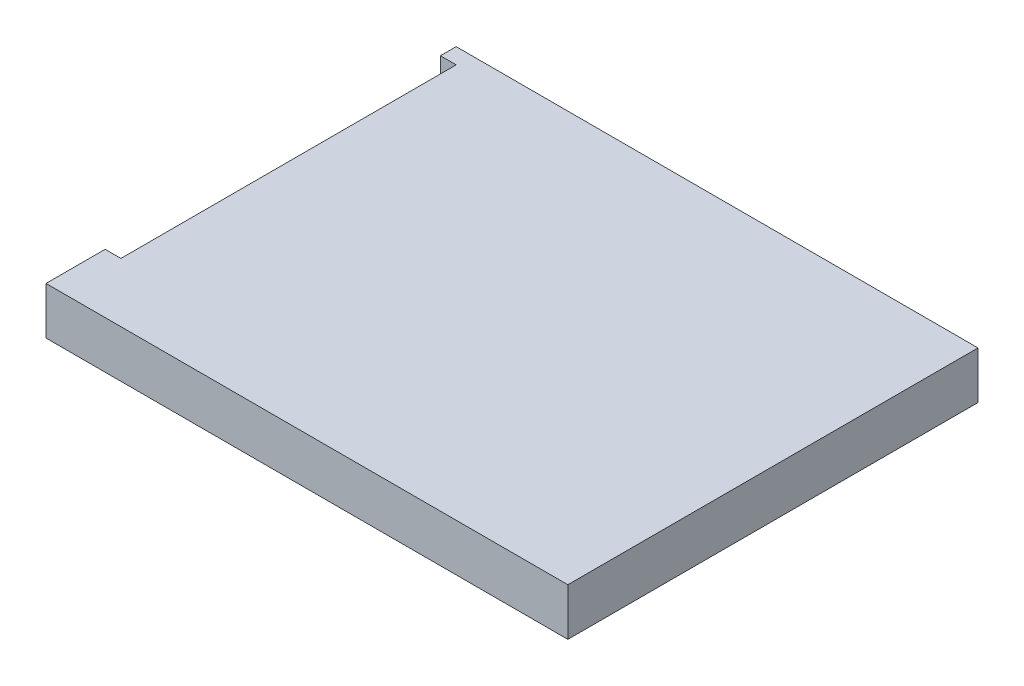
SolidWorks part; units mm, degrees
ref_plane "Front Plane" through (0, 0, 0) normal (0, 0, 1) x (1, 0, 0)
ref_plane "Top Plane" through (0, 0, 0) normal (0, 1, 0) x (1, 0, 0)
ref_plane "Right Plane" through (0, 0, 0) normal (1, 0, 0) x (0, 0, -1)
sketch "Sketch1" plane through (0, 0, 0) normal (0, 1, 0) x (1, 0, 0)
  line L1 (-108.0657, 72.5277) -> (101.9923, 72.5277)
  line L2 (-108.0657, 72.5277) -> (-108.0657, -92.5723)
  line L3 (-108.0657, -92.5723) -> (101.9923, -92.5723)
  line L4 (101.9923, 72.5277) -> (101.9923, -92.5723)
  dimension "D1" = 165.1
  dimension "D2" = 210.058
extrude "Boss-Extrude1" add sketch "Sketch1" along normal blind 19.05
sketch "Sketch2" plane through (0, 19.05, 0) normal (0, 1, 0) x (1, 0, 0)
  line L0 (-101.7157, 72.5277) -> (-101.7157, -92.5723) construction
  line L1 (101.9923, 72.5277) -> (-108.0657, 72.5277) construction
  line L2 (-108.0657, -92.5723) -> (101.9923, -92.5723) construction
  line L3 (-43.0777, 71.5338) -> (-43.0777, -92.5723) construction
  line L4 (-108.0657, 66.1777) -> (101.9923, 66.1777) construction
  line L5 (-108.0657, 72.5277) -> (-108.0657, -92.5723) construction
  line L6 (101.9923, -92.5723) -> (101.9923, 72.5277) construction
  line L7 (-108.0657, -68.7725) -> (102.9724, -68.7725) construction
  line L9 (-108.0657, 66.1777) -> (-101.7157, 66.1777)
  line L10 (-108.0657, 66.1777) -> (-108.0657, -68.7725)
  line L11 (-108.0657, -68.7725) -> (-101.7157, -68.7725)
  line L12 (-101.7157, 66.1777) -> (-101.7157, -68.7725)
  dimension "D1" = 6.35
  dimension "D2" = 6.35
  dimension "D3" = 134.9502
extrude "Cut-Extrude1" cut sketch "Sketch2" against normal blind 12.7
